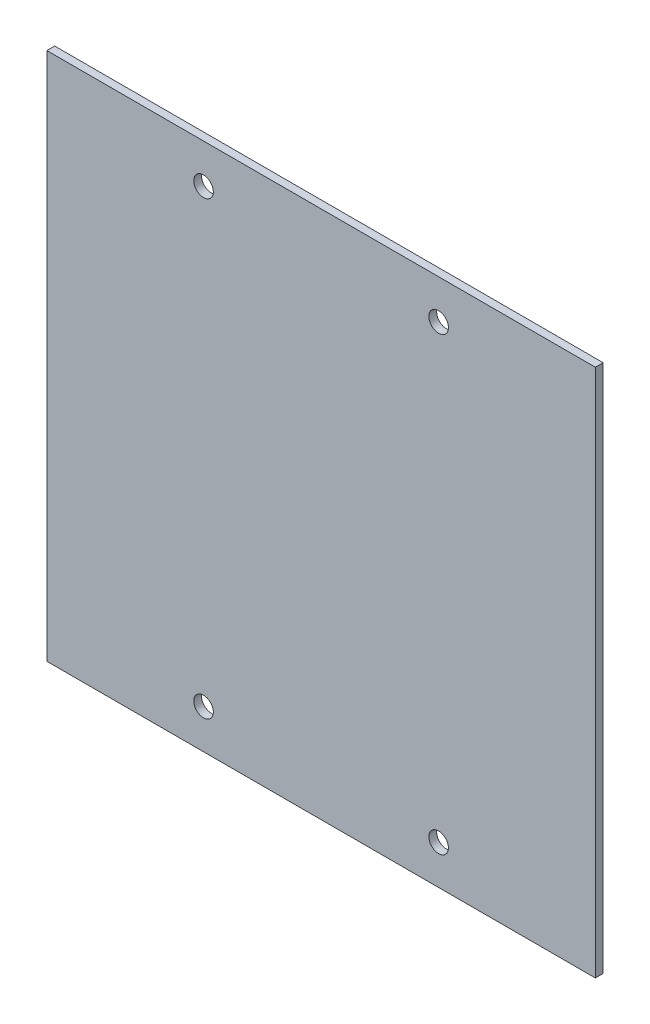
SolidWorks part; units mm, degrees
ref_plane "Ön Düzlem" through (0, 0, 0) normal (0, 0, 1) x (1, 0, 0)
ref_plane "Üst Düzlem" through (0, 0, 0) normal (0, 1, 0) x (1, 0, 0)
ref_plane "Sağ Düzlem" through (0, 0, 0) normal (1, 0, 0) x (0, 0, -1)
sketch "Çizim1" plane through (0, 0, 0) normal (0, 0, 1) x (1, 0, 0)
  line L0 (40, 135) -> (40, 0) construction
  line L1 (0, 0) -> (140, 0)
  line L2 (0, 0) -> (0, 135)
  line L3 (0, 135) -> (140, 135)
  line L4 (140, 0) -> (140, 135)
  line L5 (100, 135) -> (100, 0) construction
  line L6 (0, 125) -> (140, 125) construction
  line L7 (0, 10) -> (140, 10) construction
  circle A0 centre (40, 125) radius 2.5
  circle A1 centre (100, 125) radius 2.5
  circle A2 centre (40, 10) radius 2.5
  circle A3 centre (100, 10) radius 2.5
  dimension "D6" = 10
  dimension "D8" = 5
  dimension "D1" = 40
  dimension "D2" = 40
  dimension "D3" = 10
  dimension "D4" = 10
  dimension "D5" = 135
  dimension "D7" = 140
extrude "Yükseklik-Ekstrüzyon1" add sketch "Çizim1" along normal blind 2
